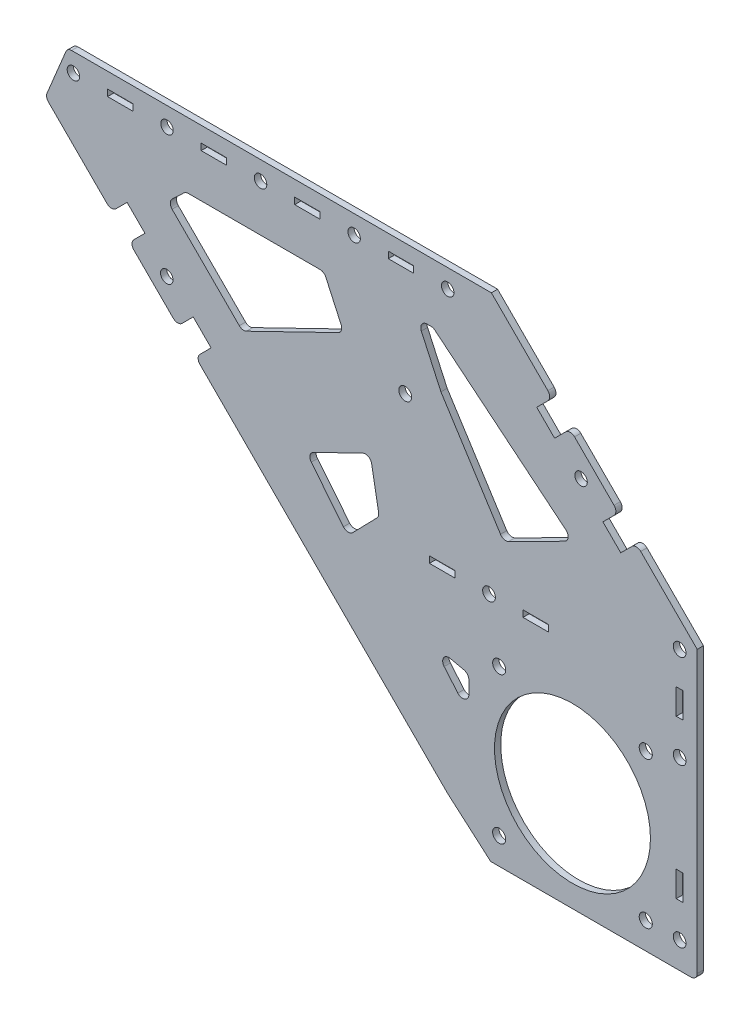
SolidWorks part; units mm, degrees
ref_plane "前视基准面" through (0, 0, 0) normal (0, 0, 1) x (1, 0, 0)
ref_plane "上视基准面" through (0, 0, 0) normal (0, 1, 0) x (1, 0, 0)
ref_plane "右视基准面" through (0, 0, 0) normal (1, 0, 0) x (0, 0, -1)
sketch "草图1" plane through (0, 0, 0) normal (0, 0, 1) x (1, 0, 0)
  line L261 (47.0274, 35.0547) -> (47.0274, 15.0547) construction
  line L315 (7.0274, -4.999) -> (20.8108, -16.957)
  line L316 (-52.9726, 135.0547) -> (-52.9726, 126.7057) construction
  line L332 (-112.9726, 135.0547) -> (-97.9726, 135.0547) construction
  line L334 (-42.0226, 136.1047) -> (-33.9226, 136.1047)
  line L335 (-42.0226, 136.1047) -> (-42.0226, 134.0047)
  line L336 (-42.0226, 134.0047) -> (-33.9226, 134.0047)
  line L337 (-33.9226, 136.1047) -> (-33.9226, 134.0047)
  line L338 (-42.0226, 136.1047) -> (-33.9226, 134.0047) construction
  line L339 (-42.0226, 134.0047) -> (-33.9226, 136.1047) construction
  line L389 (-114.8842, 141.0547) -> (21.0274, 141.0547)
  line L390 (-22.9726, 135.0547) -> (-22.9726, 144.5851) construction
  line L395 (-37.9726, 135.0547) -> (-7.9726, 135.0547) construction
  line L418 (87.0274, 75.0547) -> (21.0274, 141.0547) construction
  line L419 (-3.9226, 134.0047) -> (-12.0226, 136.1047) construction
  line L420 (-3.9226, 136.1047) -> (-12.0226, 134.0047) construction
  line L421 (7.0274, 135.0547) -> (-7.9726, 135.0547) construction
  line L422 (-12.0226, 136.1047) -> (-12.0226, 134.0047)
  line L423 (-3.9226, 134.0047) -> (-12.0226, 134.0047)
  line L424 (-3.9226, 136.1047) -> (-3.9226, 134.0047)
  line L443 (-3.9226, 136.1047) -> (-12.0226, 136.1047)
  line L444 (-102.0226, 136.1047) -> (-93.9226, 134.0047) construction
  line L445 (-102.0226, 134.0047) -> (-93.9226, 136.1047) construction
  line L446 (7.0274, -4.999) -> (-139.0436, 141.0882) construction
  line L447 (-67.9726, 135.0547) -> (-97.9726, 135.0547) construction
  line L448 (-104.2577, 114.7679) -> (-83.0445, 93.5547) construction
  line L449 (-63.9226, 134.0047) -> (-72.0226, 136.1047) construction
  line L483 (-63.9226, 136.1047) -> (-72.0226, 134.0047) construction
  line L515 (47.0274, 35.0547) -> (47.0274, 135.0547) construction
  line L516 (47.0274, 135.0547) -> (-52.9726, 135.0547) construction
  line L517 (-102.0226, 136.1047) -> (-93.9226, 136.1047)
  line L518 (-102.0226, 136.1047) -> (-102.0226, 134.0047)
  line L519 (-102.0226, 134.0047) -> (-93.9226, 134.0047)
  line L520 (-93.9226, 136.1047) -> (-93.9226, 134.0047)
  line L521 (-72.0226, 136.1047) -> (-72.0226, 134.0047)
  line L522 (-63.9226, 134.0047) -> (-72.0226, 134.0047)
  line L523 (-63.9226, 136.1047) -> (-63.9226, 134.0047)
  line L524 (-63.9226, 136.1047) -> (-72.0226, 136.1047)
  line L556 (21.4033, 132.1936) -> (81.3921, 72.2048) construction
  line L557 (54.0274, 108.0547) -> (35.0674, 89.0947) construction
  line L558 (42.7844, 112.2974) -> (35.5719, 116.54) construction
  line L559 (56.7851, 95.3268) -> (62.5127, 89.5993)
  line L576 (56.7851, 95.3268) -> (58.2701, 96.8117)
  line L577 (58.2701, 96.8117) -> (63.9976, 91.0842) construction
  line L578 (62.5127, 89.5993) -> (63.9976, 91.0842)
  line L579 (56.7851, 95.3268) -> (63.9976, 91.0842) construction
  line L580 (58.2701, 96.8117) -> (62.5127, 89.5993) construction
  line L581 (41.2995, 110.8124) -> (37.0569, 118.0249) construction
  line L582 (35.5719, 116.54) -> (37.0569, 118.0249)
  line L583 (42.7844, 112.2974) -> (37.0569, 118.0249) construction
  line L584 (41.2995, 110.8124) -> (42.7844, 112.2974)
  line L585 (41.2995, 110.8124) -> (35.5719, 116.54)
  line L586 (60.3914, 93.2055) -> (59.6489, 92.463) construction
  line L587 (39.1782, 114.4187) -> (38.4357, 113.6762) construction
  line L589 (20.2758, 57.0547) -> (5.2758, 57.0547) construction
  line L605 (-26.0184, 28.0504) -> (-21.7793, 32.2895) construction
  line L607 (-83.0445, 93.5547) -> (-87.2854, 89.3138) construction
  line L621 (-83.0445, 93.5547) -> (-61.8313, 72.3415) construction
  line L623 (73.2276, -16.9644) -> (87.0274, -16.9644)
  line L624 (23.5274, -8.4453) -> (70.5274, -8.4453) construction
  line L631 (-97.2574, 106.2827) -> (-91.5298, 100.5551) construction
  line L632 (-82.9726, 135.0547) -> (-82.9726, 64.2144) construction
  line L633 (-97.2574, 106.2827) -> (-95.7724, 107.7676)
  line L638 (-22.9726, 135.0547) -> (-22.9726, 124.9547) construction
  line L639 (87.0274, -16.9644) -> (87.0274, 75.0547)
  line L640 (20.2758, 57.0547) -> (20.2758, 57.6954) construction
  line L641 (9.3758, 56.0047) -> (1.1758, 56.0047)
  line L642 (9.3758, 56.0047) -> (9.3758, 58.1047)
  line L643 (9.3758, 58.1047) -> (1.1758, 58.1047)
  line L644 (1.1758, 56.0047) -> (1.1758, 58.1047)
  line L645 (9.3758, 56.0047) -> (1.1758, 58.1047) construction
  line L646 (9.3758, 58.1047) -> (1.1758, 56.0047) construction
  line L647 (31.1758, 58.1047) -> (39.3758, 56.0047) construction
  line L648 (31.1758, 56.0047) -> (39.3758, 58.1047) construction
  line L649 (39.3758, 56.0047) -> (39.3758, 58.1047)
  line L650 (31.1758, 58.1047) -> (39.3758, 58.1047)
  line L651 (31.1758, 56.0047) -> (31.1758, 58.1047)
  line L652 (31.1758, 56.0047) -> (39.3758, 56.0047)
  line L653 (-6.5853, 99.2267) -> (-61.8313, 72.3415) construction
  line L654 (-104.2577, 114.7679) -> (-82.9726, 135.0547) construction
  line L655 (-82.9726, 135.0547) -> (-22.9726, 135.0547) construction
  line L656 (-22.9726, 135.0547) -> (-6.5853, 99.2267) construction
  line L657 (-61.8313, 72.3415) -> (-104.2577, 114.7679) construction
  line L658 (-26.3178, 106.3059) -> (-58.7833, 90.5067)
  line L659 (-58.7833, 90.5067) -> (-82.7867, 114.5102)
  line L660 (-82.7867, 114.5102) -> (-76.9693, 120.0547)
  line L661 (-76.9693, 120.0547) -> (-32.6063, 120.0547)
  line L662 (-32.6063, 120.0547) -> (-26.3178, 106.3059)
  line L663 (70.998, 82.5989) -> (20.2758, 57.0547) construction
  line L664 (70.998, 82.5989) -> (7.0274, 135.0547) construction
  line L665 (7.0274, 135.0547) -> (-22.9726, 135.0547) construction
  line L667 (47.2997, 85.2197) -> (24.9262, 73.9522)
  line L668 (4.8626, 105.452) -> (24.9262, 73.9522)
  line L669 (-2.7313, 122.0547) -> (4.8626, 105.452)
  line L670 (2.3789, 122.0547) -> (-2.7313, 122.0547)
  line L671 (47.2997, 85.2197) -> (2.3789, 122.0547)
  line L672 (1.1758, 56.0047) -> (-6.5853, 99.2267) construction
  line L673 (-61.8313, 72.3415) -> (-26.0184, 28.0504) construction
  line L674 (-26.0184, 28.0504) -> (1.1758, 56.0047) construction
  line L675 (-14.9502, 60.9397) -> (-17.8458, 77.065)
  line L676 (-17.8458, 77.065) -> (-38.3086, 67.1069)
  line L677 (-38.3086, 67.1069) -> (-24.9829, 50.6265)
  line L678 (-24.9829, 50.6265) -> (-14.9502, 60.9397)
  line L679 (23.8026, -6.8752) -> (23.8026, 39.5844) construction
  line L680 (23.8026, 39.5844) -> (-24.9829, 50.6265) construction
  line L681 (-24.9829, 50.6265) -> (23.8026, -6.8752) construction
  line L682 (2.0144, 34.263) -> (13.8026, 20.3686)
  line L683 (13.8026, 20.3686) -> (13.8026, 31.5948)
  line L684 (13.8026, 31.5948) -> (2.0144, 34.263)
  line L685 (23.5274, -8.4453) -> (23.5274, 38.5547) construction
  line L686 (23.5274, 38.5547) -> (70.5274, 38.5547) construction
  line L687 (70.5274, -8.4453) -> (70.5274, 38.5547) construction
  line L688 (23.5274, -8.4453) -> (70.5274, 38.5547) construction
  line L689 (23.5274, 38.5547) -> (70.5274, -8.4453) construction
  line L690 (-91.5298, 100.5551) -> (-90.0449, 102.04)
  line L691 (-95.7724, 107.7676) -> (-90.0449, 102.04)
  line L692 (-97.2574, 106.2827) -> (-90.0449, 102.04) construction
  line L693 (-91.5298, 100.5551) -> (-95.7724, 107.7676) construction
  line L694 (-76.0442, 85.0695) -> (-68.8317, 80.8268) construction
  line L695 (-70.3166, 79.3419) -> (-74.5592, 86.5544) construction
  line L696 (-68.8317, 80.8268) -> (-74.5592, 86.5544)
  line L697 (-76.0442, 85.0695) -> (-74.5592, 86.5544)
  line L698 (-70.3166, 79.3419) -> (-68.8317, 80.8268)
  line L699 (-70.3166, 79.3419) -> (-76.0442, 85.0695) construction
  line L700 (-70.3166, 79.3419) -> (-73.815, 75.8434)
  line L701 (-76.0442, 85.0695) -> (-79.5426, 81.571)
  line L702 (-91.5298, 100.5551) -> (-95.0283, 97.0566)
  line L703 (-97.2574, 106.2827) -> (-100.7558, 102.7842)
  line L704 (-121.9553, 123.9837) -> (-100.7558, 102.7842)
  line L705 (-95.0283, 97.0566) -> (-87.2854, 89.3138)
  line L706 (-87.2854, 89.3138) -> (-79.5426, 81.571)
  line L707 (-73.815, 75.8434) -> (7.0274, -4.999)
  line L708 (37.0569, 118.0249) -> (40.557, 121.5251)
  line L709 (40.557, 121.5251) -> (21.0274, 141.0547)
  line L710 (42.7844, 112.2974) -> (46.2846, 115.7976)
  line L711 (46.2846, 115.7976) -> (54.0274, 108.0547)
  line L712 (54.0274, 108.0547) -> (61.7717, 100.3104)
  line L713 (61.7717, 100.3104) -> (58.2701, 96.8117)
  line L714 (63.9976, 91.0842) -> (67.4978, 94.5844)
  line L715 (67.4978, 94.5844) -> (87.0274, 75.0547)
  line L716 (20.8108, -16.957) -> (73.2276, -16.9644)
  line L717 (-6.5853, 99.2267) -> (20.2758, 57.0547) construction
  line L719 (81.3921, -8.4453) -> (81.3921, 72.2048) construction
  line L721 (-121.9553, 123.9837) -> (-114.8842, 141.0547)
  line L722 (80.2921, 53.1048) -> (82.4921, 53.1048)
  line L723 (80.2921, 53.1048) -> (80.2921, 61.3048)
  line L724 (80.2921, 61.3048) -> (82.4921, 61.3048)
  line L725 (82.4921, 53.1048) -> (82.4921, 61.3048)
  line L726 (80.2921, 53.1048) -> (82.4921, 61.3048) construction
  line L727 (80.2921, 61.3048) -> (82.4921, 53.1048) construction
  line L728 (80.2921, 2.4547) -> (82.4921, 2.4547)
  line L729 (80.2921, 2.4547) -> (80.2921, 10.6547)
  line L730 (80.2921, 10.6547) -> (82.4921, 10.6547)
  line L731 (82.4921, 2.4547) -> (82.4921, 10.6547)
  line L732 (80.2921, 2.4547) -> (82.4921, 10.6547) construction
  line L733 (80.2921, 10.6547) -> (82.4921, 2.4547) construction
  circle A39 centre (-52.9726, 135.0547) radius 2
  circle A42 centre (47.0274, 15.0547) radius 25
  circle A49 centre (-22.9726, 135.0547) radius 2
  circle A69 centre (7.0274, 135.0547) radius 2
  circle A92 centre (-112.9726, 135.0547) radius 2
  circle A93 centre (-82.9726, 135.0547) radius 2
  circle A98 centre (49.7848, 103.8121) radius 2
  arc A115 (-114.8842, 141.0547) -> (-121.9553, 123.9837) centre (-114.8842, 131.0547) ccw construction
  circle A116 centre (-83.0445, 93.5547) radius 2
  circle A121 centre (20.2758, 57.0547) radius 2.05
  circle A122 centre (-6.5853, 99.2267) radius 2.05
  circle A123 centre (70.5274, -8.4453) radius 2.1
  circle A124 centre (23.5274, -8.4453) radius 2.1
  circle A125 centre (23.5274, 38.5547) radius 2.1
  circle A126 centre (70.5274, 38.5547) radius 2.1
  circle A127 centre (81.3921, 72.2048) radius 2.05
  circle A128 centre (81.3921, -8.4453) radius 2.05
  circle A129 centre (81.3921, 42.2048) radius 2.05
  point P5 (210.9534, 218.4629)
  point P6 (288.6284, 218.4629)
  point P51 (-93.6511, 104.1613)
  point P54 (-105.4726, 135.0547)
  point P60 (60.3914, 93.2055)
  point P83 (-93.6511, 104.1613)
  point P98 (81.3921, 57.2048)
  point P115 (47.016, -39.6917)
  point P147 (-72.4379, 82.9481)
  point P152 (81.3921, 6.5547)
  dimension "D3" = 50
  dimension "D5" = 4
  dimension "D4" = 47
  dimension "D6" = 15
  dimension "D7" = 2.1
  dimension "D12" = 4
  dimension "D19" = 29.4043
  dimension "D20" = 2.2
  dimension "D22" = 4
  dimension "D8" = 30
  dimension "D28" = 8.2
  dimension "D26" = 10
  dimension "D17" = 10.1
  dimension "D29" = 42
  dimension "D30" = 15
  dimension "D31" = 80.6501
  dimension "D18" = 8.1
  dimension "D15" = 8.2
  dimension "D27" = 30
  dimension "D9" = 15
  dimension "D10" = 15
  dimension "D11" = 8.1
  dimension "D13" = 2.1
  dimension "D14" = 6
  dimension "D16" = 41.5
  dimension "D21" = 6
  dimension "D23" = 15
  dimension "D24" = 15
  dimension "D25" = 2.1
  dimension "D32" = 8.2
  dimension "D33" = 2.1
  dimension "D34" = 120
  dimension "D35" = 70
  dimension "D36" = 15
  dimension "D37" = 13
  dimension "D38" = 15
  dimension "D39" = 10
extrude "凸台-拉伸1" add sketch "草图1" along normal blind 2
fillet "圆角2" radius 2 27 edges at (-76.9693, 120.0547, 1) (-82.7867, 114.5102, 1) (-32.6063, 120.0547, 1) (-26.3178, 106.3059, 1) (-58.7833, 90.5067, 1) (-17.8458, 77.065, 1) (-14.9502, 60.9397, 1) (-24.9829, 50.6265, 1) (-38.3086, 67.1069, 1) (47.2997, 85.2197, 1) (24.9262, 73.9522, 1) (2.3789, 122.0547, 1) (-2.7313, 122.0547, 1) (13.8026, 31.5948, 1) (2.0144, 34.263, 1) (13.8026, 20.3686, 1) (87.0274, -16.9644, 1) (-100.7558, 102.7842, 1) (-95.0283, 97.0566, 1) (-79.5426, 81.571, 1) (-73.815, 75.8434, 1) (67.4978, 94.5844, 1) (61.7717, 100.3104, 1) (46.2846, 115.7976, 1) (40.557, 121.5251, 1) (-114.8842, 141.0547, 1) (-121.9553, 123.9837, 1)
